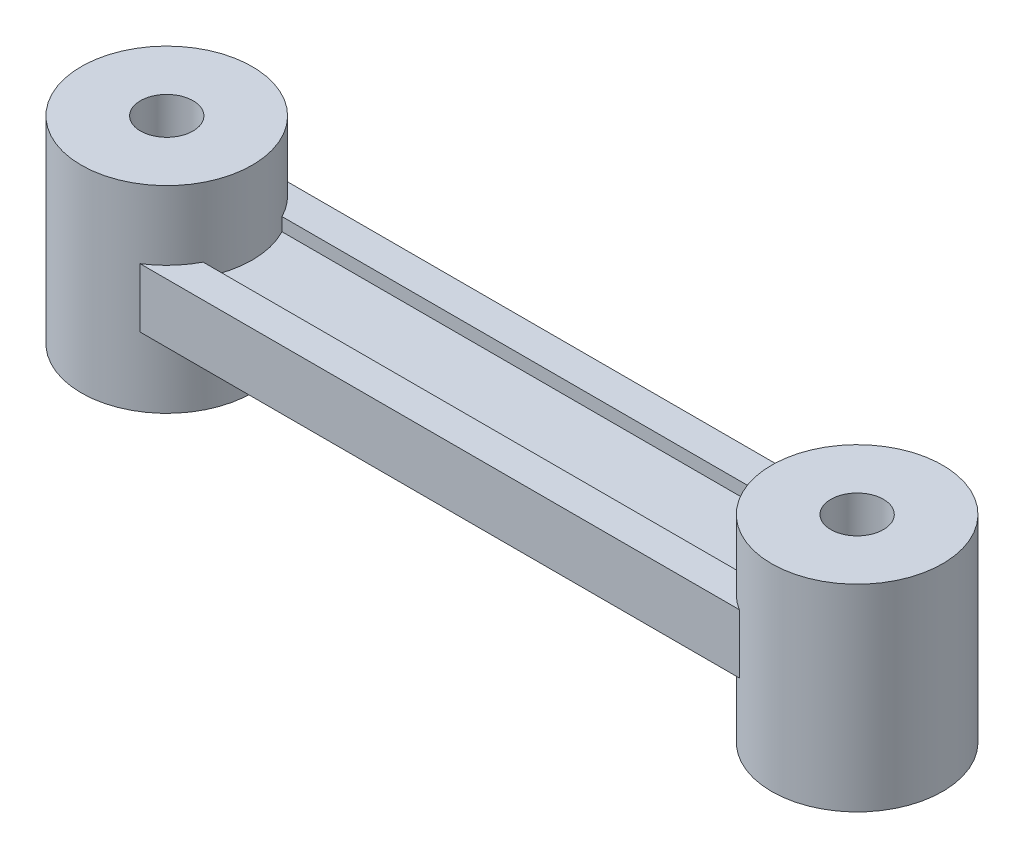
SolidWorks part; units mm, degrees
ref_plane "Спереди" through (0, 0, 0) normal (0, 0, 1) x (1, 0, 0)
ref_plane "Сверху" through (0, 0, 0) normal (0, 1, 0) x (1, 0, 0)
ref_plane "Справа" through (0, 0, 0) normal (1, 0, 0) x (0, 0, -1)
sketch "Эскиз1" plane through (0, 0, 0) normal (0, 1, 0) x (1, 0, 0)
  line L0 (0, 0) -> (-131, 0) construction
  circle A0 centre (-118, 0) radius 13
  circle A1 centre (-13, 0) radius 13
  circle A2 centre (-118, 0) radius 4
  circle A3 centre (-13, 0) radius 4
  dimension "D2" = 26
  dimension "D3" = 26
  dimension "D4" = 8
  dimension "D5" = 8
  dimension "D1" = 131
extrude "Бобышка-Вытянуть1" add sketch "Эскиз1" along normal mid plane 30
sketch "Эскиз2" plane through (0, 0, 0) normal (0, 1, 0) x (1, 0, 0)
  line L0 (-134.54, 0) -> (5.8565, 0) construction
  line L1 (-111.0718, 11) -> (-19.9282, 11)
  line L2 (-111.0718, -11) -> (-19.9282, -11)
  arc A0 (-111.0718, -11) -> (-111.0718, 11) centre (-118, 0) ccw
  arc A1 (-19.9282, 11) -> (-19.9282, -11) centre (-13, 0) ccw
extrude "Бобышка-Вытянуть2" add sketch "Эскиз2" along normal mid plane 9
sketch "Эскиз4" plane through (0, 4.5, 0) normal (0, 1, 0) x (1, 0, 0)
  line L0 (-118, 0) -> (6.9337, 0) construction
  line L1 (-106.4674, 6) -> (-24.5326, 6)
  line L2 (-106.4674, -6) -> (-24.5326, -6)
  arc A0 (-106.4674, -6) -> (-106.4674, 6) centre (-118, 0) ccw
  arc A1 (-24.5326, 6) -> (-24.5326, -6) centre (-13, 0) ccw
extrude "Вырез-Вытянуть1" cut sketch "Эскиз4" against normal blind 2
mirror "Зеркальное отражение1" about plane through (0, 0, 0) normal (0, 1, 0) of "Вырез-Вытянуть1"
